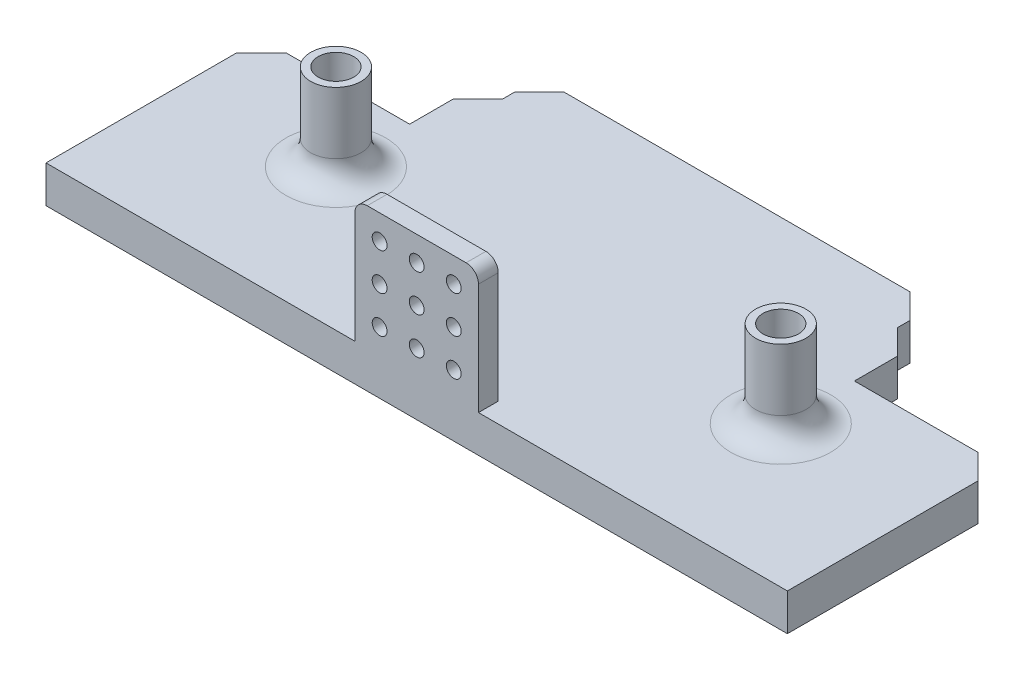
SolidWorks part; units mm, degrees
ref_plane "Front Plane" through (0, 0, 0) normal (0, 0, 1) x (1, 0, 0)
ref_plane "Top Plane" through (0, 0, 0) normal (0, 1, 0) x (1, 0, 0)
ref_plane "Right Plane" through (0, 0, 0) normal (1, 0, 0) x (0, 0, -1)
sketch "Sketch1" plane through (0, 0, 0) normal (0, 1, 0) x (1, 0, 0)
  line L1 (-75, 28.66) -> (75, 28.66)
  line L2 (-75, 28.66) -> (-75, -28.66)
  line L3 (-75, -28.66) -> (75, -28.66)
  line L4 (75, 28.66) -> (75, -28.66)
  line L5 (-75, 28.66) -> (75, -28.66) construction
  line L6 (-75, -28.66) -> (75, 28.66) construction
  point P0 (0, 0)
  dimension "D1" = 57.32
  dimension "D2" = 150
extrude "Boss-Extrude1" add sketch "Sketch1" along normal blind 7.5
sketch "Sketch2" plane through (0, 7.5, 0) normal (0, 1, 0) x (1, 0, 0)
  line L0 (-75, 0) -> (75, 0) construction
  line L1 (-75, 28.66) -> (-75, -28.66) construction
  line L2 (75, -28.66) -> (75, 28.66) construction
  circle A0 centre (-45, 0) radius 5.1
  circle A1 centre (45, 0) radius 5.1
  dimension "D1" = 30
  dimension "D2" = 30
extrude "Boss-Extrude2" add sketch "Sketch2" along normal blind 17.5
fillet "Fillet1" radius 5 2 edges at (45, 7.5, 5.1) (-45, 7.5, 5.1)
sketch "Sketch3" plane through (0, 25, 0) normal (0, 1, 0) x (1, 0, 0)
  circle A0 centre (-45, 0) radius 3.6
  circle A1 centre (45, 0) radius 3.6
extrude "Cut-Extrude1" cut sketch "Sketch3" against normal blind 25
sketch "Sketch4" plane through (0, 0, -28.66) normal (0, 0, -1) x (-1, 0, 0)
  line L0 (-75, 0) -> (75, 0) construction
  line L1 (-75, 7.5) -> (-45, 7.5)
  line L2 (-75, 7.5) -> (-75, 0)
  line L3 (-75, 0) -> (-45, 0)
  line L4 (-45, 7.5) -> (-45, 0)
  line L6 (75, 7.5) -> (45, 7.5)
  line L7 (75, 7.5) -> (75, 0)
  line L8 (75, 0) -> (45, 0)
  line L9 (45, 7.5) -> (45, 0)
  dimension "D1" = 30
  dimension "D2" = 30
extrude "Cut-Extrude2" cut sketch "Sketch4" against normal blind 13.75
chamfer "Chamfer1" distance 5 angle 45 4 edges at (75, 3.75, -14.91) (45, 3.75, -28.66) (-45, 3.75, -28.66) (-75, 3.75, -14.91)
sketch "Sketch5" plane through (0, 0, -28.66) normal (0, 0, -1) x (-1, 0, 0)
  line L1 (-40, 7.5) -> (40, 7.5)
  line L2 (-40, 7.5) -> (-40, 0)
  line L3 (-40, 0) -> (40, 0)
  line L4 (40, 7.5) -> (40, 0)
extrude "Boss-Extrude3" add sketch "Sketch5" along normal blind 7.5
chamfer "Chamfer2" distance 5 angle 45 2 edges at (40, 3.75, -36.16) (-40, 3.75, -36.16)
sketch "Sketch6" plane through (0, 0, -36.16) normal (0, 0, -1) x (-1, 0, 0)
  line L0 (-35, 3.75) -> (35, 3.75) construction
  line L1 (-35, 7.5) -> (-35, 0) construction
  line L2 (35, 0) -> (35, 7.5) construction
  circle A0 centre (-15, 3.75) radius 1.5
  circle A1 centre (15, 3.75) radius 1.5
  point P10 (0, 3.75)
  dimension "D1" = 15
  dimension "D2" = 15
extrude "Cut-Extrude3" cut sketch "Sketch6" against normal blind 7.5
sketch "Sketch7" plane through (0, 7.5, 0) normal (0, 1, 0) x (1, 0, 0)
  line L0 (0, -28.66) -> (0, 36.16) construction
  line L1 (-75, -28.66) -> (75, -28.66) construction
  line L2 (-35, 36.16) -> (35, 36.16) construction
  line L3 (-43.2004, -23.66) -> (-25.6652, -23.66) construction
  line L4 (-12.5, -24.66) -> (-12.5, -28.66) construction
  line L5 (12.5, -24.66) -> (12.5, -28.66) construction
  line L7 (-12.5, -24.66) -> (12.5, -24.66)
  line L8 (-12.5, -24.66) -> (-12.5, -28.66)
  line L9 (-12.5, -28.66) -> (12.5, -28.66)
  line L10 (12.5, -24.66) -> (12.5, -28.66)
  dimension "D1" = 5
  dimension "D2" = 12.5
  dimension "D3" = 12.5
  dimension "D4" = 4
extrude "Boss-Extrude4" add sketch "Sketch7" along normal blind 25
sketch "Sketch8" plane through (0, 0, 24.66) normal (0, 0, -1) x (-1, 0, 0)
  line L0 (-12.5, 31.25) -> (12.5, 31.25) construction
  line L1 (-12.5, 32.5) -> (-12.5, 7.5) construction
  line L2 (12.5, 32.5) -> (12.5, 7.5) construction
  line L3 (-12.5, 32.5) -> (12.5, 32.5) construction
  line L4 (-12.5, 8.75) -> (12.5, 8.75) construction
  line L5 (-11.25, 32.5) -> (-11.25, 8.75) construction
  line L6 (11.25, 32.5) -> (11.25, 8.75) construction
  line L7 (0, 31.25) -> (0, 8.75) construction
  line L8 (-3.75, 31.25) -> (-3.75, 8.75) construction
  line L9 (3.75, 31.25) -> (3.75, 8.75) construction
  line L10 (-11.25, 23.75) -> (11.25, 23.75) construction
  line L11 (-11.25, 16.25) -> (11.25, 16.25) construction
  line L12 (-7.5, 31.25) -> (-7.5, 8.75) construction
  line L13 (7.5, 31.25) -> (7.5, 8.75) construction
  line L14 (-11.25, 27.5) -> (11.25, 27.5) construction
  line L15 (-11.25, 12.5) -> (11.25, 12.5) construction
  circle A0 centre (-7.5, 20) radius 1.5
  circle A1 centre (0, 20) radius 1.5
  circle A2 centre (-7.5, 27.5) radius 1.5
  circle A3 centre (0, 27.5) radius 1.5
  circle A4 centre (7.5, 27.5) radius 1.5
  circle A5 centre (7.5, 20) radius 1.5
  circle A6 centre (-7.5, 12.5) radius 1.5
  circle A7 centre (0, 12.5) radius 1.5
  circle A8 centre (7.5, 12.5) radius 1.5
  dimension "D10" = 3.75
  dimension "D12" = 3.75
  dimension "D1" = 1.25
  dimension "D2" = 1.25
  dimension "D3" = 1.25
  dimension "D4" = 1.25
  dimension "D5" = 3.75
  dimension "D6" = 3.75
  dimension "D7" = 7.5
  dimension "D8" = 7.5
  dimension "D9" = 3.75
  dimension "D11" = 3.75
extrude "Cut-Extrude4" cut sketch "Sketch8" against normal blind 5
fillet "Fillet2" radius 2.5 2 edges at (12.5, 32.5, 26.66) (-12.5, 32.5, 26.66)
